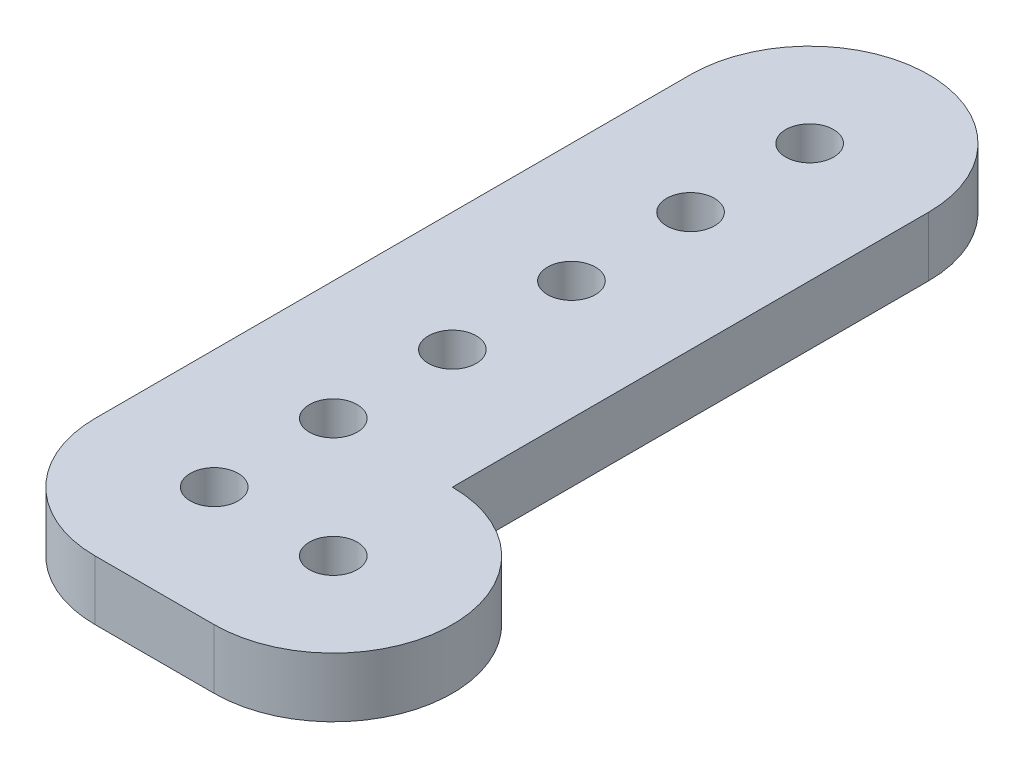
SolidWorks part; units mm, degrees
material "Birch Plywood"
ref_plane "Front Plane" through (0, 0, 0) normal (0, 0, 1) x (1, 0, 0)
ref_plane "Top Plane" through (0, 0, 0) normal (0, 1, 0) x (1, 0, 0)
ref_plane "Right Plane" through (0, 0, 0) normal (1, 0, 0) x (0, 0, -1)
sketch "Sketch1" plane through (0, 0, 0) normal (0, 1, 0) x (1, 0, 0)
  line L0 (0, 12.7) -> (0, 0) construction
  line L1 (0, 0) -> (12.7, 0) construction
  line L2 (12.7, 0) -> (0, 0) construction
  line L3 (12.7, -12.7) -> (0, -12.7)
  line L4 (12.7, 12.7) -> (0, 12.7)
  line L5 (0, 0) -> (0, 63.5) construction
  line L6 (-12.7, 0) -> (-12.7, 63.5)
  line L7 (12.7, 0) -> (12.7, 63.5)
  circle A0 centre (0, 0) radius 2.5527
  circle A1 centre (12.7, 0) radius 2.5527
  circle A6 centre (0, 12.7) radius 2.5527
  circle A7 centre (0, 25.4) radius 2.5527
  circle A8 centre (0, 38.1) radius 2.5527
  circle A9 centre (0, 50.8) radius 2.5527
  circle A10 centre (0, 63.5) radius 2.5527
  arc A11 (12.7, -12.7) -> (12.7, 12.7) centre (12.7, 0) ccw
  arc A12 (0, 12.7) -> (0, -12.7) centre (0, 0) ccw
  arc A13 (-12.7, 0) -> (12.7, 0) centre (0, 0) ccw
  arc A14 (12.7, 63.5) -> (-12.7, 63.5) centre (0, 63.5) ccw
  point P4 (0, 0)
  point P28 (0, 31.75)
  dimension "D1" = 5.1054
  dimension "D6" = 12.7
  dimension "D3" = 12.7
  dimension "D4" = 12.7
  dimension "D2" = 2
  dimension "D5" = 6
extrude "Boss-Extrude1" add sketch "Sketch1" along normal mid plane 6.35 contours A13 L3 A11 L7 A1 | A12 A13 A1 L7 L4 A6 A0 | L7 A14 L6 A12 A6 L4 A7 A8 A9 A10
